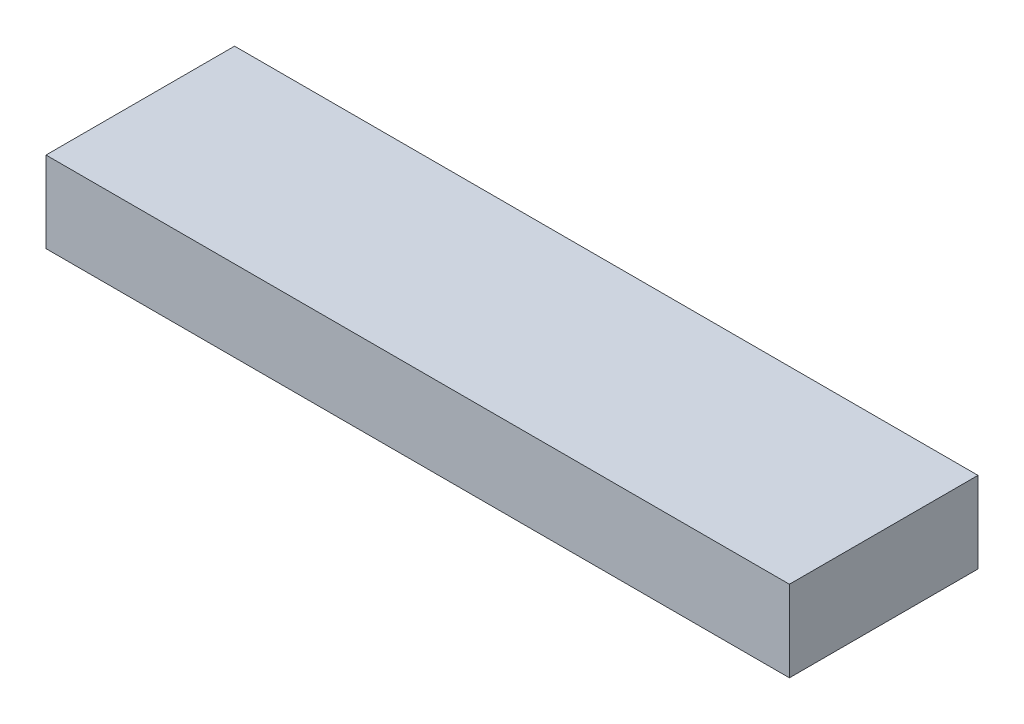
SolidWorks part; units mm, degrees
ref_plane "前视基准面" through (0, 0, 0) normal (0, 0, 1) x (1, 0, 0)
ref_plane "上视基准面" through (0, 0, 0) normal (0, 1, 0) x (1, 0, 0)
ref_plane "右视基准面" through (0, 0, 0) normal (1, 0, 0) x (0, 0, -1)
sketch "草图1" plane through (0, 0, 0) normal (0, 0, 1) x (1, 0, 0)
  line L1 (-19.71, 4.3) -> (19.71, 4.3)
  line L2 (-19.71, 4.3) -> (-19.71, 0)
  line L3 (-19.71, 0) -> (19.71, 0)
  line L4 (19.71, 4.3) -> (19.71, 0)
  dimension "D1" = 39.42
  dimension "D2" = 4.3
  dimension "D3" = 19.71
extrude "凸台-拉伸1" add sketch "草图1" along normal blind 10
